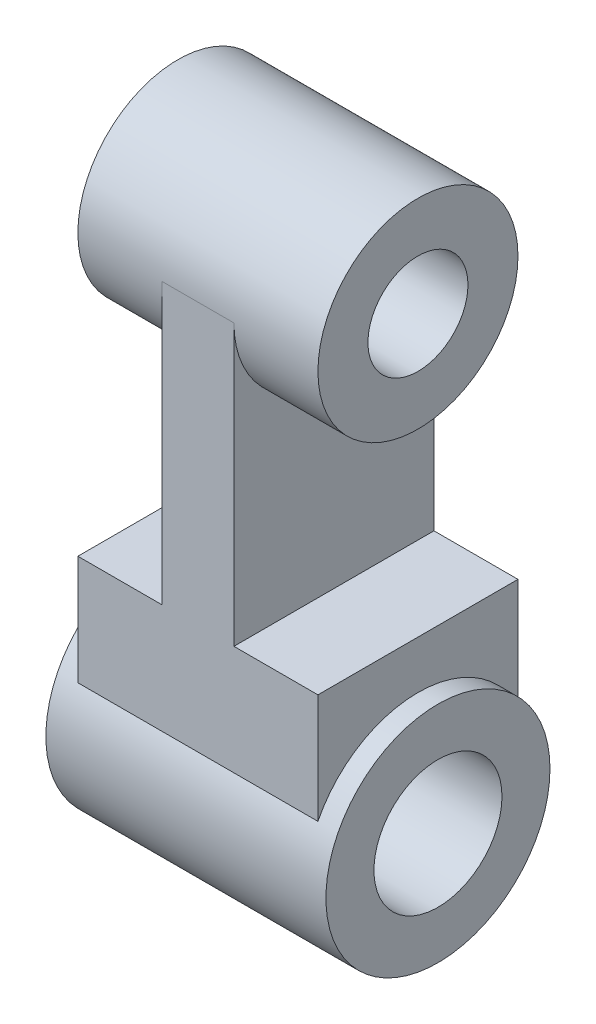
SolidWorks part; units mm, degrees
ref_plane "Front Plane" through (0, 0, 0) normal (0, 0, 1) x (1, 0, 0)
ref_plane "Top Plane" through (0, 0, 0) normal (0, 1, 0) x (1, 0, 0)
ref_plane "Right Plane" through (0, 0, 0) normal (1, 0, 0) x (0, 0, -1)
sketch "Sketch1" plane through (0, 0, 0) normal (1, 0, 0) x (0, 0, -1)
  circle A0 centre (0, 0) radius 16
  circle A1 centre (0, 0) radius 28
  dimension "D1" = 56
  dimension "D2" = 32
extrude "Boss-Extrude1" add sketch "Sketch1" along normal mid plane 70
sketch "Sketch2" plane through (0, 0, 0) normal (1, 0, 0) x (0, 0, -1)
  line L0 (0, 0) -> (43.3356, 0) construction
  line L1 (0, 0) -> (0, 40) construction
  line L2 (-25, 40) -> (25, 40)
  line L3 (-25, 40) -> (-25, 12.6095)
  line L4 (25, 40) -> (25, 12.6095)
  circle A0 centre (0, 0) radius 28 construction
  circle A2 centre (0, 0) radius 28
  arc A3 (25, 12.6095) -> (-25, 12.6095) centre (0, 0) ccw
  point P7 (0, 40)
  dimension "D1" = 50
  dimension "D2" = 40
  dimension "D3" = 0
extrude "Boss-Extrude3" add sketch "Sketch2" along normal mid plane 60
sketch "Sketch3" plane through (0, 0, 0) normal (1, 0, 0) x (0, 0, -1)
  line L0 (-25, 40) -> (-25, 110)
  line L1 (25, 40) -> (25, 110)
  line L2 (-25, 110) -> (25, 110) construction
  line L6 (25, 12.6095) -> (25, 40)
  line L7 (25, 40) -> (-25, 40)
  line L8 (-25, 40) -> (-25, 12.6095)
  line L10 (25, 40) -> (-25, 40)
  arc A1 (-25, 110) -> (25, 110) centre (0, 110) ccw
  arc A3 (25, 12.6095) -> (-25, 12.6095) centre (0, 0) ccw
  dimension "D1" = 0
  dimension "D2" = 50
  dimension "D3" = 70
extrude "Boss-Extrude4" add sketch "Sketch3" along normal mid plane 18
sketch "Sketch5" plane through (0, 0, 0) normal (1, 0, 0) x (0, 0, -1)
  line L0 (-25, 110) -> (25, 110) construction
  arc A0 (-25, 110) -> (25, 110) centre (0, 110) ccw construction
  circle A1 centre (0, 110) radius 12.5
  circle A2 centre (0, 110) radius 25
  dimension "D1" = 50
  dimension "D2" = 25
extrude "Boss-Extrude5" add sketch "Sketch5" along normal mid plane 60
